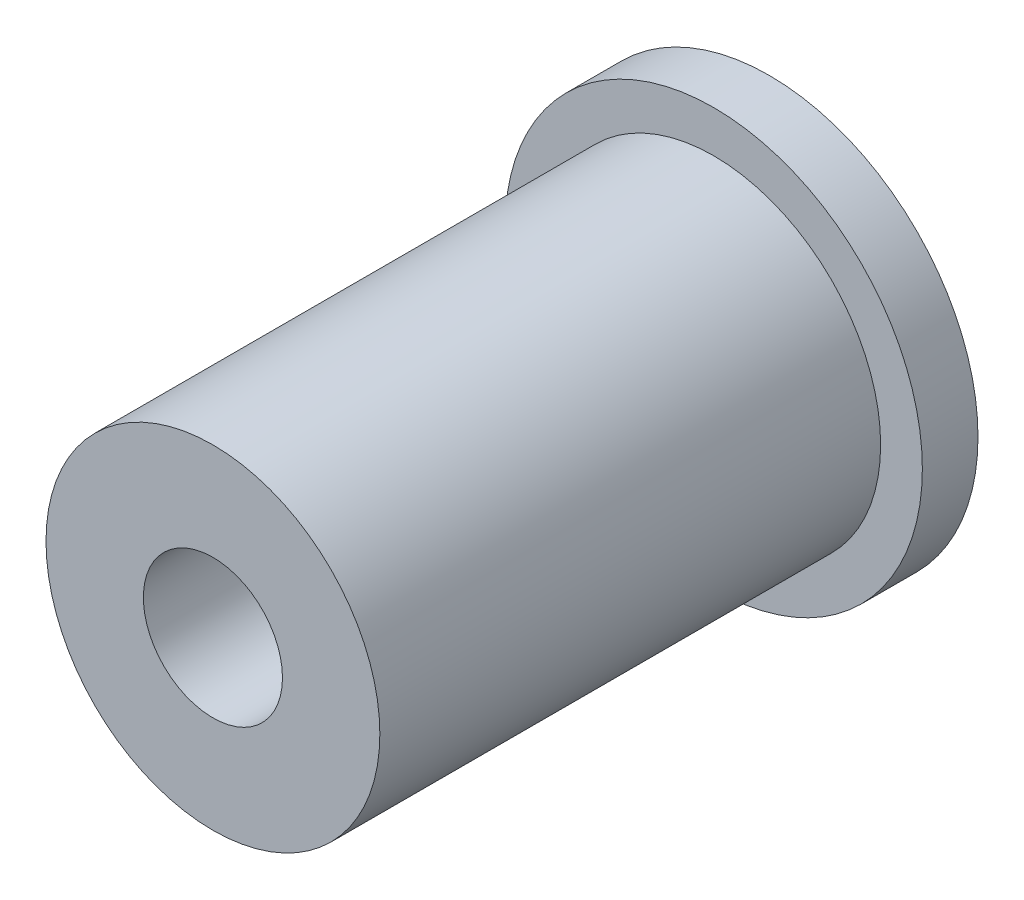
SolidWorks part; units mm, degrees
ref_plane "Front Plane" through (0, 0, 0) normal (0, 0, 1) x (1, 0, 0)
ref_plane "Top Plane" through (0, 0, 0) normal (0, 1, 0) x (1, 0, 0)
ref_plane "Right Plane" through (0, 0, 0) normal (1, 0, 0) x (0, 0, -1)
sketch "Sketch1" plane through (0, 0, 0) normal (0, 0, 1) x (1, 0, 0)
  circle A0 centre (0, 0) radius 7.5
  circle A1 centre (0, 0) radius 2.5
  dimension "D1" = 15
  dimension "D2" = 5
extrude "Boss-Extrude1" add sketch "Sketch1" along normal blind 2
sketch "Sketch3" plane through (0, 0, 2) normal (0, 0, 1) x (1, 0, 0)
  circle A0 centre (0, 0) radius 2.5
  circle A1 centre (0, 0) radius 6
  dimension "D1" = 12
extrude "Boss-Extrude2" add sketch "Sketch3" along normal blind 18
